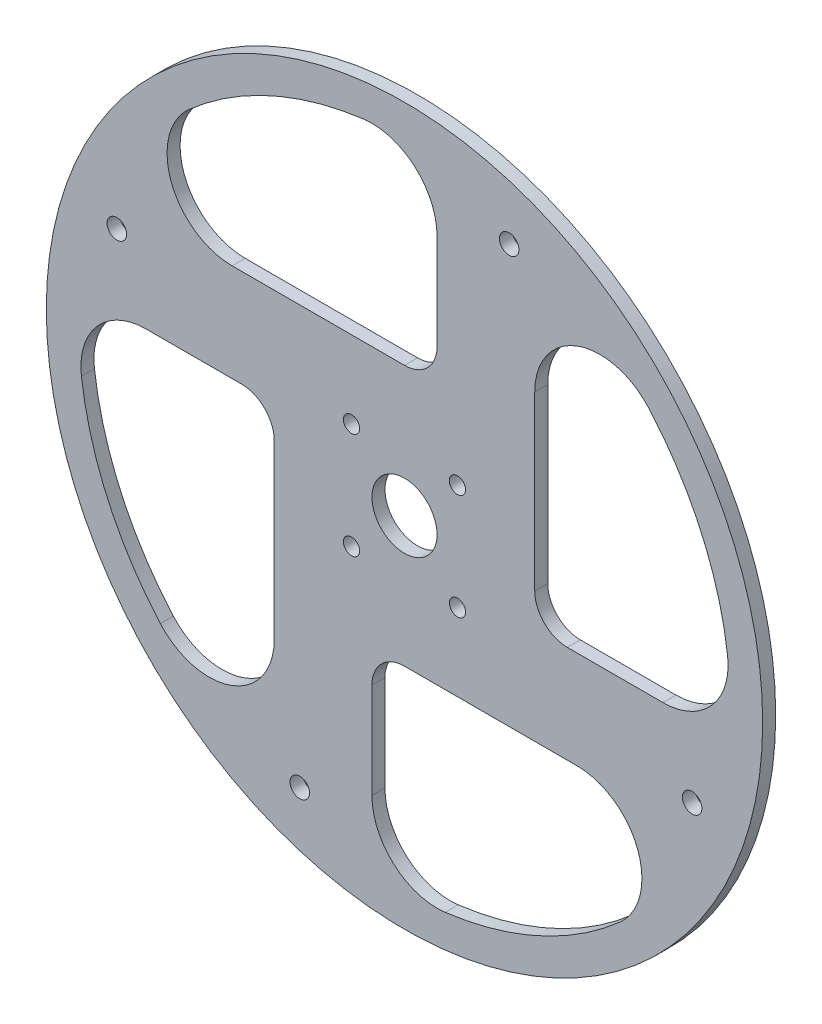
SolidWorks part; units mm, degrees
ref_plane "前视基准面" through (0, 0, 0) normal (0, 0, 1) x (1, 0, 0)
ref_plane "上视基准面" through (0, 0, 0) normal (0, 1, 0) x (1, 0, 0)
ref_plane "右视基准面" through (0, 0, 0) normal (1, 0, 0) x (0, 0, -1)
other "Configuration Table"
sketch "草图1" plane through (0, 0, 0) normal (0, 0, 1) x (1, 0, 0)
  line L0 (0, 0) -> (0, 16.9097) construction
  line L5 (0, 0) -> (-8.1317, 8.1317) construction
  line L10 (0, 20) -> (-26.4575, 20)
  line L11 (-19.3649, 5) -> (-49.7494, 5) construction
  line L18 (7.3863, 0) -> (-76.4712, 0) construction
  line L19 (-25, 5) -> (-39.6863, 5)
  line L20 (0, 0) -> (-44.1656, 16.0749) construction
  line L24 (20, 0) -> (20, 26.4575)
  line L25 (5, 25) -> (5, 39.6863)
  line L26 (0, 0) -> (8.1317, 8.1317) construction
  line L28 (0, 0) -> (16.0749, 44.1656) construction
  line L29 (0, -20) -> (26.4575, -20)
  line L30 (25, -5) -> (39.6863, -5)
  line L31 (0, 0) -> (8.1317, -8.1317) construction
  line L33 (0, 0) -> (44.1656, -16.0749) construction
  line L34 (-20, 0) -> (-20, -26.4575)
  line L35 (-5, -25) -> (-5, -39.6863)
  line L36 (0, 0) -> (-8.1317, -8.1317) construction
  line L38 (0, 0) -> (-16.0749, -44.1656) construction
  line L39 (5, 19.3649) -> (5, 49.7494) construction
  line L40 (-5, -19.3649) -> (-5, -49.7494) construction
  line L41 (19.3649, -5) -> (49.7494, -5) construction
  circle A0 centre (0, 0) radius 55
  circle A2 centre (0, 0) radius 11.5 construction
  circle A3 centre (-8.1317, 8.1317) radius 1.25
  circle A4 centre (8.1317, 8.1317) radius 1.25
  circle A5 centre (8.1317, -8.1317) radius 1.25
  circle A6 centre (-8.1317, -8.1317) radius 1.25
  circle A7 centre (0, 0) radius 5
  arc A11 (-19.3649, 5) -> (-20, 0) centre (0, 0) ccw construction
  arc A13 (-49.6078, -6.25) -> (-33.0719, 37.5) centre (0, 0) ccw construction
  arc A18 (-20, 0) -> (-25, 5) centre (-25, 0) ccw
  arc A19 (-39.6863, 5) -> (-49.6078, -6.25) centre (-39.6863, -5) ccw
  arc A20 (-26.4575, 20) -> (-33.0719, 37.5) centre (-26.4575, 30) cw
  circle A21 centre (0, 0) radius 50 construction
  circle A22 centre (-44.1656, 16.0749) radius 1.5
  arc A23 (0, 20) -> (5, 25) centre (0, 25) ccw
  arc A24 (5, 39.6863) -> (-6.25, 49.6078) centre (-5, 39.6863) ccw
  arc A25 (20, 26.4575) -> (37.5, 33.0719) centre (30, 26.4575) cw
  circle A26 centre (16.0749, 44.1656) radius 1.5
  arc A27 (-33.0719, 37.5) -> (-6.25, 49.6078) centre (0, 0) cw
  arc A28 (20, 0) -> (25, -5) centre (25, 0) ccw
  arc A29 (39.6863, -5) -> (49.6078, 6.25) centre (39.6863, 5) ccw
  arc A30 (26.4575, -20) -> (33.0719, -37.5) centre (26.4575, -30) cw
  circle A31 centre (44.1656, -16.0749) radius 1.5
  arc A32 (37.5, 33.0719) -> (50, 0) centre (0, 0) cw
  arc A33 (0, -20) -> (-5, -25) centre (0, -25) ccw
  arc A34 (-5, -39.6863) -> (6.25, -49.6078) centre (5, -39.6863) ccw
  arc A35 (-20, -26.4575) -> (-37.5, -33.0719) centre (-30, -26.4575) cw
  circle A36 centre (-16.0749, -44.1656) radius 1.5
  arc A37 (33.0719, -37.5) -> (0, -50) centre (0, 0) cw
  arc A38 (-5, -19.3649) -> (0, -20) centre (0, 0) ccw construction
  arc A39 (5, 19.3649) -> (0, 20) centre (0, 0) ccw construction
  arc A40 (19.3649, -5) -> (20, 0) centre (0, 0) ccw construction
  arc A41 (-37.5, -33.0719) -> (-49.6078, -6.25) centre (0, 0) cw
  point P18 (0, 0)
  point P27 (-39.6863, -5)
  point P28 (-20, 0)
  point P33 (0, 0)
  point P34 (0, 0)
  point P36 (0, 0)
  point P37 (0, 0)
  point P38 (0, 0)
  point P47 (0, 0)
  point P48 (0, 20)
  point P49 (0, 0)
  point P50 (-30.9416, -5.9416)
  point P51 (0, 0)
  point P55 (-38.6018, 11.6097)
  point P57 (0, 0)
  point P66 (0, 0)
  point P74 (0, 0)
  point P83 (0, 0)
  point P91 (0, 0)
  point P97 (0, 0)
  dimension "D1" = 110
  dimension "D2" = 5
  dimension "D3" = 23
  dimension "D4" = 2.5
  dimension "D7" = 10
  dimension "D8" = 4
  dimension "D11" = 10
  dimension "D12" = 10
  dimension "D13" = 3
  dimension "D15" = 20
  dimension "D5" = 45
  dimension "D9" = 15
  dimension "D10" = 20
  dimension "D14" = 47
  dimension "D6" = 4
extrude "凸台-拉伸1" add sketch "草图1" along normal blind 2 contours A0 A36 A31 A26 A22 A7 A6 A5 A4 A3 A20 A27 A24 L25 A23 L10 A25 A32 A29 L30 A28 L24 A30 A37 A34 L35 A33 L29 A35 A41 A19 L19 A18 L34
